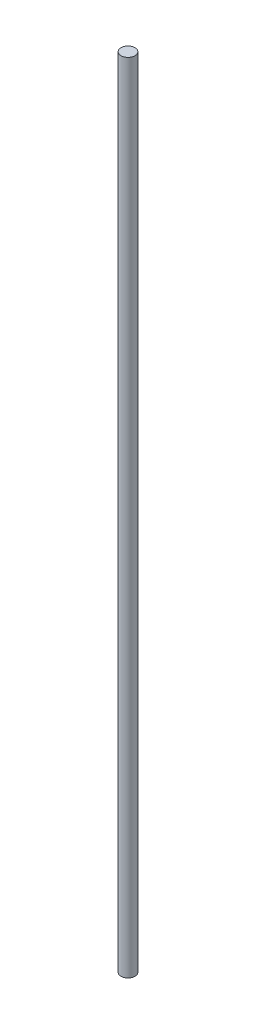
SolidWorks part; units mm, degrees
ref_plane "Front Plane" through (0, 0, 0) normal (0, 0, 1) x (1, 0, 0)
ref_plane "Top Plane" through (0, 0, 0) normal (0, 1, 0) x (1, 0, 0)
ref_plane "Right Plane" through (0, 0, 0) normal (1, 0, 0) x (0, 0, -1)
sketch "Sketch1" plane through (0, 0, 0) normal (0, 1, 0) x (1, 0, 0)
  circle A0 centre (0, 0) radius 4
  dimension "D1" = 8
extrude "Boss-Extrude1" add sketch "Sketch1" along normal blind 457.2
